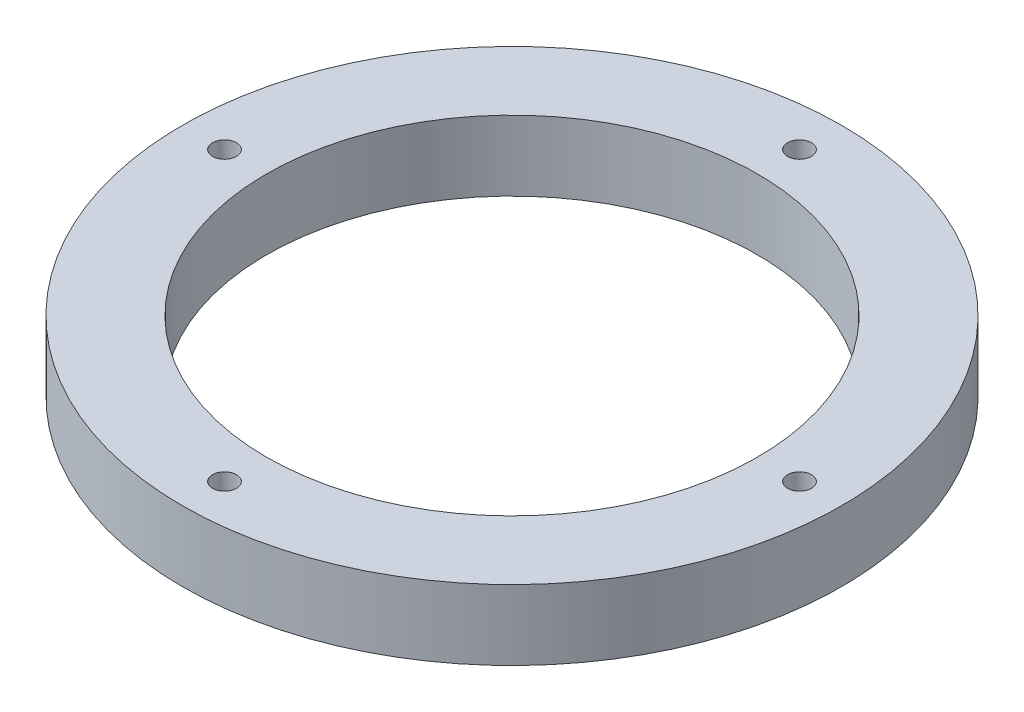
SolidWorks part; units mm, degrees
ref_plane "Piano frontale" through (0, 0, 0) normal (0, 0, 1) x (1, 0, 0)
ref_plane "Piano superiore" through (0, 0, 0) normal (0, 1, 0) x (1, 0, 0)
ref_plane "Piano destro" through (0, 0, 0) normal (1, 0, 0) x (0, 0, -1)
sketch "Schizzo1" plane through (0, 0, 0) normal (0, 1, 0) x (1, 0, 0)
  circle A0 centre (0, 0) radius 35
  circle A1 centre (0, 0) radius 47
  dimension "D1" = 70
  dimension "D2" = 12
extrude "Estrusione-Estrusione1" add sketch "Schizzo1" along normal blind 10
hole_wizard "Foro svasato per Vite M3-1" positions "Schizzo3D1" profile "Schizzo3" countersink size "M3" standard "ISO"
sketch3d "Schizzo3D1"
  line L0 (0, 0, -41) -> (0, 0, 41) construction
  line L2 (41, 0, 0) -> (-41, 0, 0) construction
  circle A2 centre (0, 0, 0) radius 41 construction
  point P36 (0, 41, 0)
  point P38 (0, 0, -41)
  point P58 (41, 0, 0)
  point P60 (0, 0, 41)
  point P62 (-41, 0, 0)
  point P64 (0, 0, 0)
  point P65 (0, 0, 0)
  point P66 (0, 0, 0)
  dimension "D1" = 82
sketch "Schizzo3" plane through (-41, 0, 0) normal (1, 0, 0) x (0, 0, -1)
  line L0 (0, 0) -> (0, 189.0215)
  line L1 (0, 189.0215) -> (1.7, 188)
  line L2 (1.7, 188) -> (1.7, 1.45)
  line L3 (1.7, 1.45) -> (3.15, 0)
  line L5 (3.15, 0) -> (0, 0)
  line L6 (-1.7, 1.45) -> (-3.15, 0) construction
  line L10 (0, 189.0215) -> (-1.7, 188) construction
  line L11 (0, -6.35) -> (0, 107.95) construction
  dimension "Hole Dia." = 3.4
  dimension "Hole Depth" = 188
  dimension "Near C'Sink Dia." = 6.3
  dimension "Near C'Sink Angle" = 90
  dimension "Drill Angle" = 118
sketch "Schizzo4" plane through (0, 10, 0) normal (0, 1, 0) x (1, 0, 0)
  point P0 (0, -41)
  point P1 (-41, 0)
  point P3 (0, 41)
  point P5 (41, 0)
  point P7 (0, 0)
  point P9 (0, 0)
  point P10 (0, 0)
  point P11 (0, 0)
  point P12 (0, 0)
  point P13 (-41, 0)
  point P15 (0, -41)
  point P17 (41.5062, -1.0196)
  point P18 (41, 0)
  point P19 (0, 41)
  point P20 (41.7932, -0.651)
